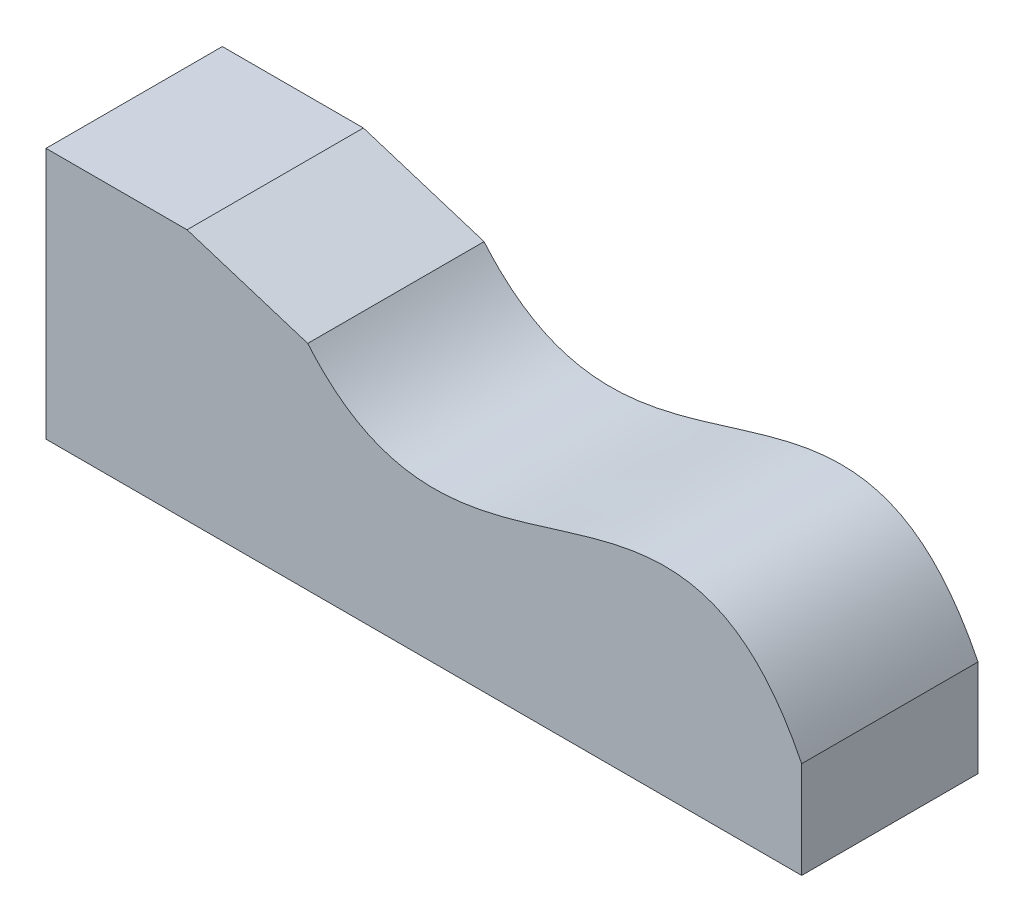
SolidWorks part; units mm, degrees
ref_plane "前基準面" through (0, 0, 0) normal (0, 0, 1) x (1, 0, 0)
ref_plane "上基準面" through (0, 0, 0) normal (0, 1, 0) x (1, 0, 0)
ref_plane "右基準面" through (0, 0, 0) normal (1, 0, 0) x (0, 0, -1)
sketch "草圖2" plane through (0, 0, 0) normal (0, 0, 1) x (1, 0, 0)
  line L0 (0, 0) -> (0, 50)
  line L1 (0, 50) -> (28, 50)
  line L2 (28, 50) -> (51.9563, 42.4433)
  line L3 (150, 19.2094) -> (150, 0)
  line L4 (150, 0) -> (0, 0)
  spline S0 degree 3 poles (51.9563, 42.4433) (83.8971, 4.556) (124.6273, 70.2572) (150, 19.2094) knots 0 0 0 0 1 1 1 1
  point P6 (51.9563, 42.4433)
  dimension "D3" = 112
  dimension "D1" = 50
  dimension "D2" = 28
  dimension "D4" = 150
extrude "填料-伸長1" add sketch "草圖2" along normal blind 35
